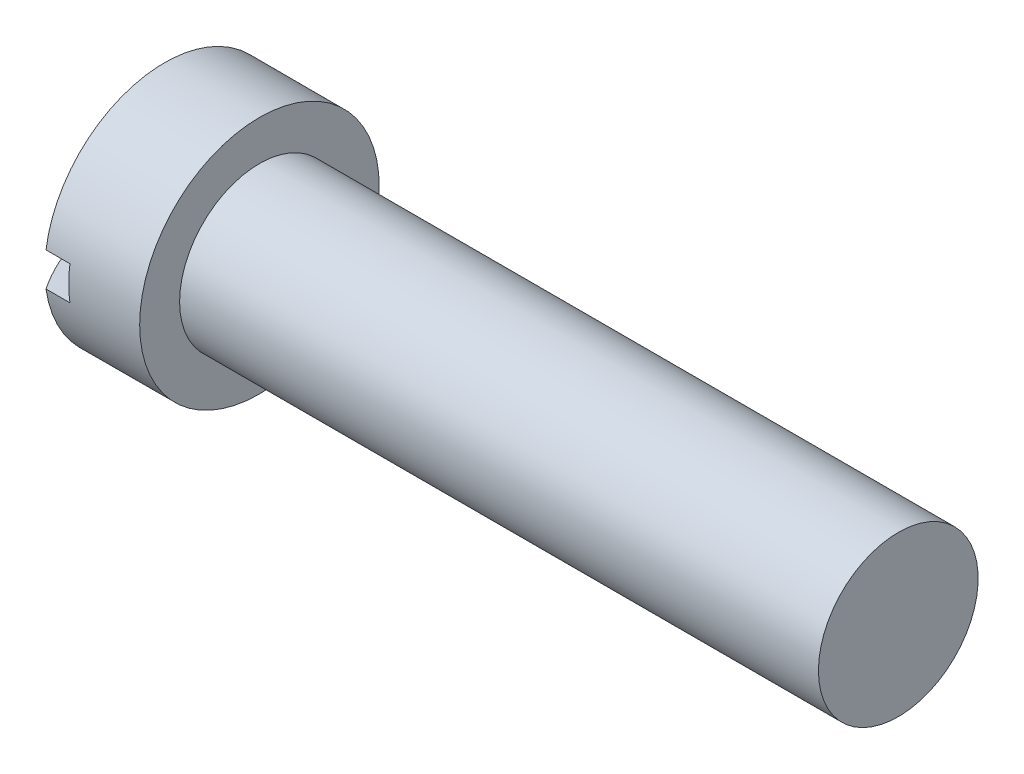
SolidWorks part; units mm, degrees
ref_plane "Plane1" through (0, 0, 0) normal (0, 0, 1) x (1, 0, 0)
ref_plane "Plane2" through (0, 0, 0) normal (0, 1, 0) x (1, 0, 0)
ref_plane "Plane3" through (0, 0, 0) normal (1, 0, 0) x (0, 0, -1)
sketch "BodySke" plane through (0, 0, 0) normal (0, 0, 1) x (1, 0, 0)
  line L0 (10.4648, 6.35) -> (10.4648, 9.525)
  line L1 (10.4648, 9.525) -> (2.921, 9.525)
  line L2 (-25.4, 0) -> (127, 0) construction
  line L3 (61.2648, 0) -> (0, 0)
  line L4 (10.4648, 6.35) -> (61.2648, 6.35)
  line L5 (61.2648, 6.35) -> (61.2648, 0)
  line L6 (10.4648, -9.525) -> (2.921, -9.525) construction
  line L7 (10.4648, -6.35) -> (61.2648, -6.35) construction
  line L8 (11.7348, 1.2192) -> (11.7348, -0.4698) construction
  line L9 (10.4648, 1.2192) -> (10.4648, -0.4698) construction
  arc A0 (0, 0) -> (2.921, 9.525) centre (16.9904, 0) cw
  dimension "Head_ht" = 10.4648
  dimension "Diameter" = 12.7
  dimension "Length" = 50.8
  dimension "Head_dia" = 19.05
  dimension "Head_side_ht" = 7.5438
  dimension "Advance" = 1.27
  dimension "Thread_nom" = 50.8
revolve "Base-Revolve" add sketch "BodySke" angle 360 about L2
cosmetic thread "ThreadCosmetic" parameters "Thread_length"=49.53, "Thread_minor"=11.1887
sketch "Sketch2" plane through (0, 0, 0) normal (1, 0, 0) x (0, 0, -1)
  line L0 (-9.525, -1.3462) -> (-9.525, 1.3462)
  line L1 (-9.525, 1.3462) -> (9.525, 1.3462)
  line L2 (9.525, 1.3462) -> (9.525, -1.3462)
  line L3 (9.525, -1.3462) -> (-9.525, -1.3462)
  dimension "D1" = 19.05
  dimension "D2" = 9.525
  dimension "D3" = 1.3462
  dimension "Slot_width" = 2.6924
extrude "Slot" cut sketch "Sketch2" along normal blind 4.826
sketch "Sketch3" plane through (0, 0, 0) normal (1, 0, 0) x (0, 0, -1)
  line L0 (1.1557, -7.1374) -> (-1.1557, -7.1374)
  line L1 (1.1557, -7.1374) -> (1.1557, 7.1374)
  line L2 (-1.1557, 7.1374) -> (1.1557, 7.1374)
  line L3 (-1.1557, 7.1374) -> (-1.1557, -7.1374)
  dimension "D1" = 1.1557
  dimension "Cross_width" = 2.3114
  dimension "D2" = 7.1374
  dimension "Cross_dia" = 14.2748
ref_plane "Plane4" through (8.6106, 0, 0) normal (1, 0, 0) x (0, 0, -1)
sketch "Sketch4" plane through (8.6106, 0, 0) normal (1, 0, 0) x (0, 0, -1)
  line L0 (0.5778, -0.5778) -> (-0.5778, -0.5779)
  line L1 (0.5778, -0.5778) -> (0.5778, 0.5778)
  line L2 (-0.5778, 0.5778) -> (0.5778, 0.5778)
  line L3 (-0.5778, 0.5778) -> (-0.5778, -0.5779)
  dimension "D1" = 1.1557
  dimension "D2" = 0.5778
  dimension "D3" = 1.1557
  dimension "D4" = 0.5778
loft "Cross" [suppressed] cut profiles "Sketch3", "Sketch4"
pattern_circular "CirPattern1" [suppressed] count 2 every 90 about axis through (-25.4, 0, 0) along (1, 0, 0)
sketch "Sketch5" plane through (0, 0, 0) normal (0, 1, 0) x (1, 0, 0)
  line L4 (-25.4, 0) -> (127, 0) construction
  line L5 (10.4648, -6.312) -> (10.4648, 6.3337) construction
  circle A0 centre (7.2709, 0) radius 0.889
  dimension "Drilled_hole_dia" = 1.778
  dimension "D1" = 10.4648
  dimension "Drilled_hole_loc" = 3.1939
extrude "Hole" [suppressed] cut sketch "Sketch5" against normal through all and the other way through all
sketch "ThdSchSke" plane through (0, 0, 0) normal (0, 0, 1) x (1, 0, 0)
  line L0 (11.7348, -5.5943) -> (11.2057, -6.35)
  line L1 (11.7348, -5.5943) -> (12.2639, -6.35)
  line L2 (12.2639, -6.35) -> (12.2639, -7.9375)
  line L3 (-3.175, 0) -> (5.1513, 0) construction
  line L5 (12.2639, -7.9375) -> (11.2057, -7.9375)
  line L6 (11.2057, -7.9375) -> (11.2057, -6.35)
  dimension "Thread_minor" = 11.1887
  dimension "Diameter" = 12.7
  dimension "Start" = 11.7348
  dimension "SideAngle" = 55
  dimension "VeeAngle" = 70
  dimension "Overcut" = 15.875
revolve "ThreadSchematic" [suppressed] cut sketch "ThdSchSke" angle 360 about L3
pattern_linear "ThdSchPat" [suppressed]
equation "\"D1@Sketch3\" = \"Cross_width@Sketch3\" / 2"
equation "\"D2@Sketch3\" = \"Cross_dia@Sketch3\" / 2"
equation "\"D1@Sketch4\" = \"Cross_width@Sketch3\"*.5"
equation "\"D2@Sketch4\" = \"D1@Sketch4\" / 2"
equation "\"D3@Sketch4\" = \"D1@Sketch4\""
equation "\"D4@Sketch4\" = \"D2@Sketch4\""
equation "\"D1@Sketch2\" = \"Head_dia@BodySke\""
equation "\"D2@Sketch2\" = \"D1@Sketch2\" / 2"
equation "\"D3@Sketch2\" = \"Slot_width@Sketch2\" / 2"
equation "\"D1@Sketch5\" = \"Head_ht@BodySke\""
equation "\"Thread_length@ThreadCosmetic\" = ((sgn( (\"Length@BodySke\" - \"Advance@BodySke\" ) - \"Thread_nom@BodySke\" )-1)*( (\"Length@BodySke\" - \"Advance@BodySke\" ) - \"Thread_nom@BodySke\" ))/-2+ \"Thread_nom@BodySke\""
equation "\"Thread_minor@ThdSchSke\" = \"Thread_minor@ThreadCosmetic\""
equation "\"Diameter@ThdSchSke\" = \"Diameter@BodySke\""
equation "\"Overcut@ThdSchSke\" = \"Diameter@BodySke\" * 1.25"
equation "\"Start@ThdSchSke\" = \"Head_ht@BodySke\" + \"Length@BodySke\" - \"Thread_length@ThreadCosmetic\"  '---Non-countersunk---"
equation "\"Num_threads@ThdSchPat\" = int( \"Thread_length@ThreadCosmetic\" / \"Advance@BodySke\" + 0.999 )  + 1"
equation "\"Advance@ThdSchPat\" = \"Thread_length@ThreadCosmetic\" /  (\"Num_threads@ThdSchPat\" - 1) 'relax it"
